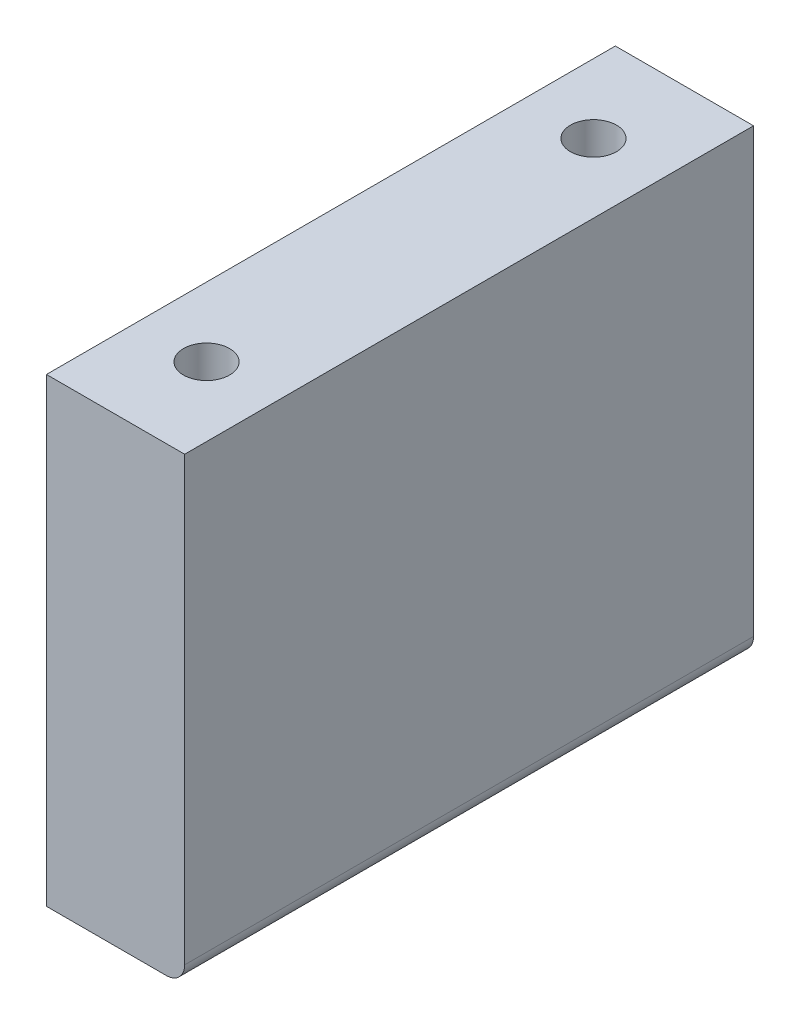
SolidWorks part; units mm, degrees
material "K110"
ref_plane "Front Plane" through (0, 0, 0) normal (0, 0, 1) x (1, 0, 0)
ref_plane "Top Plane" through (0, 0, 0) normal (0, 1, 0) x (1, 0, 0)
ref_plane "Right Plane" through (0, 0, 0) normal (1, 0, 0) x (0, 0, -1)
sketch "Sketch1" plane through (0, 0, 0) normal (0, 0, 1) x (1, 0, 0)
  line L1 (-7.5, -50) -> (7.5, -50)
  line L2 (-7.5, -50) -> (-7.5, 0)
  line L3 (-7.5, 0) -> (7.5, 0)
  line L4 (7.5, -50) -> (7.5, 0)
  point P4 (0, 0)
  dimension "D1" = 15
  dimension "D2" = 50
extrude "Boss-Extrude1" add sketch "Sketch1" along normal mid plane 61.75
fillet "Fillet1" radius 2 1 edges at (7.5, -50, 0)
hole_wizard "M6 Tapped Hole1" positions "Sketch4" profile "Sketch3" tap size "M6" standard "ISO"
sketch "Sketch4" plane through (0, 0, 0) normal (0, 1, 0) x (1, 0, 0)
  line L0 (-7.5, 0) -> (7.5, 0) construction
  line L1 (-7.5, -30.875) -> (-7.5, 30.875) construction
  line L2 (7.5, -30.875) -> (7.5, 30.875) construction
  point P0 (0, 21)
  point P2 (0, -21)
  dimension "D1" = 42
sketch "Sketch3" plane through (0, 0, -21) normal (1, 0, 0) x (0, 0, 1)
  line L0 (0, 0) -> (0, 18.5022)
  line L1 (0, 18.5022) -> (2.5, 17)
  line L2 (2.5, 17) -> (2.5, 0)
  line L5 (2.5, 0) -> (0, 0)
  line L10 (0, 18.5022) -> (-2.5, 17) construction
  line L11 (0, -6.35) -> (0, 107.95) construction
  dimension "Tap Drill Dia." = 5
  dimension "Tap Drill Depth" = 17
  dimension "Drill Angle" = 118
cosmetic thread "Hole Thread1"
cosmetic thread "Hole Thread2"
